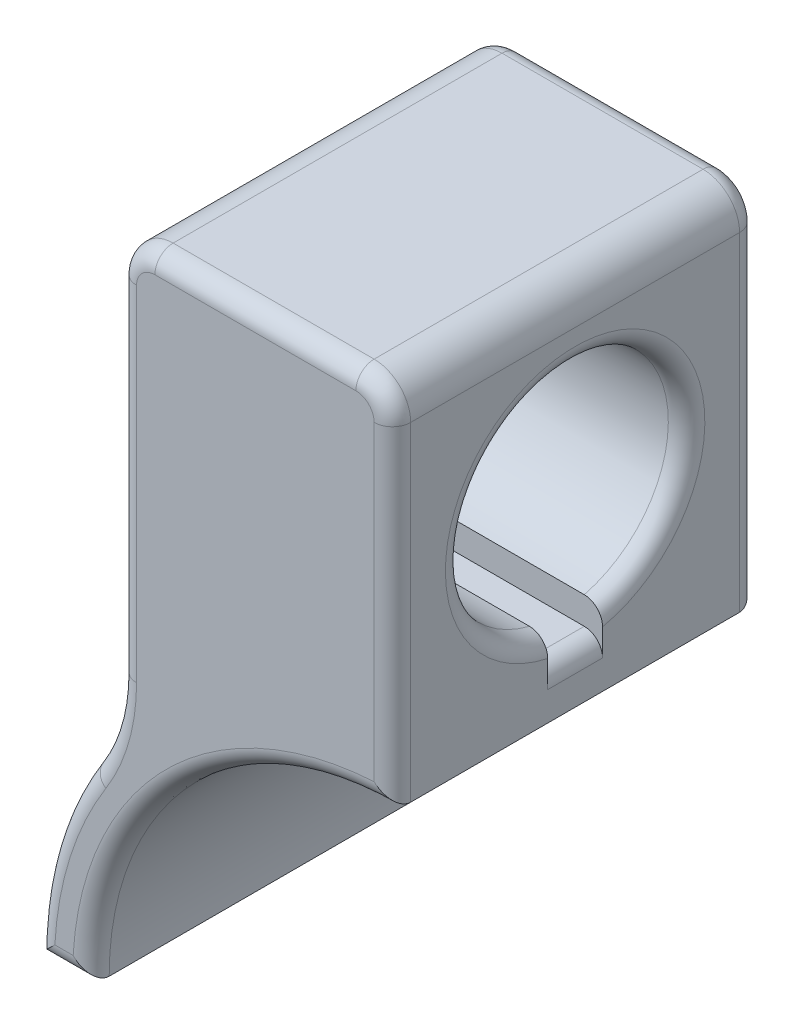
SolidWorks part; units mm, degrees
ref_plane "Front Plane" through (0, 0, 0) normal (0, 0, 1) x (1, 0, 0)
ref_plane "Top Plane" through (0, 0, 0) normal (0, 1, 0) x (1, 0, 0)
ref_plane "Right Plane" through (0, 0, 0) normal (1, 0, 0) x (0, 0, -1)
sketch "Sketch1" plane through (0, 0, 0) normal (0, 0, 1) x (1, 0, 0)
  line L0 (0, 13.7615) -> (0, -27.1597) construction
  line L1 (-27.0234, 0) -> (31.0656, 0) construction
  line L2 (-19.5, 0) -> (-16.5, 0)
  line L4 (0, 16.5) -> (0, 34.5)
  line L5 (-2, 36.5) -> (-13, 36.5)
  line L6 (-15, 34.5) -> (-15, 15.6605)
  arc A0 (0, 16.5) -> (-16.5, 0) centre (0, 0) ccw
  arc A1 (-16.5254, 10.3518) -> (-19.5, 0) centre (0, 0) ccw
  circle A2 centre (0, 0) radius 19.5 construction
  circle A3 centre (0, 0) radius 16.5 construction
  arc A4 (-15, 15.6605) -> (-16.5254, 10.3518) centre (-25, 15.6605) cw
  arc A5 (0, 34.5) -> (-2, 36.5) centre (-2, 34.5) ccw
  arc A6 (-13, 36.5) -> (-15, 34.5) centre (-13, 34.5) ccw
  point P15 (0, 0)
  point P17 (0, 16.8045)
  point P21 (0, 36.5)
  point P24 (-15, 36.5)
  dimension "D1" = 33
  dimension "D4" = 10
  dimension "D5" = 2
  dimension "D3" = 15
  dimension "D6" = 20
  dimension "D2" = 3
extrude "Boss-Extrude1" add sketch "Sketch1" along normal blind 20
sketch "Sketch2" plane through (0, 0, 0) normal (1, 0, 0) x (0, 0, -1)
  line L0 (-10, 34.5) -> (-10, 16.5) construction
  line L1 (-20, 34.5) -> (0, 34.5) construction
  line L2 (-20, 16.5) -> (0, 16.5) construction
  line L3 (-20, 36.5) -> (0, 36.5) construction
  line L4 (-11.5, 19.0873) -> (-8.5, 19.0873)
  line L5 (-8.5, 19.0873) -> (-8.5, 20.5873)
  line L6 (-11.5, 19.0873) -> (-11.5, 20.5873)
  arc A0 (-8.5, 20.5873) -> (-11.5, 20.5873) centre (-10, 26.5) ccw
  dimension "D1" = 12.2
  dimension "D2" = 10
  dimension "D3" = 1.5
  dimension "D4" = 1.5
  dimension "D5" = 1.5
extrude "Cut-Extrude1" cut sketch "Sketch2" against normal through all
fillet "Fillet1" radius 1 2 edges at (-15, 19.0873, 10) (0, 19.0873, 10)
fillet "Fillet2" radius 1 2 edges at (-15, 32.6, 10) (0, 32.6, 10)
fillet "Fillet3" radius 1 18 edges at (-18, 0, 0) (-11.6673, 11.6673, 0) (0, 25.5, 0) (-0.5858, 35.9142, 0) (-7.5, 36.5, 0) (-14.4142, 35.9142, 0) (-15, 25.0802, 0) (-15.3889, 12.8987, 0) (-18.7416, 5.3854, 0) (-15.3889, 12.8987, 20) (-15, 25.0802, 20) (-14.4142, 35.9142, 20) (-7.5, 36.5, 20) (-0.5858, 35.9142, 20) (0, 25.5, 20) (-11.6673, 11.6673, 20) (-18, 0, 20) (-18.7416, 5.3854, 20)
